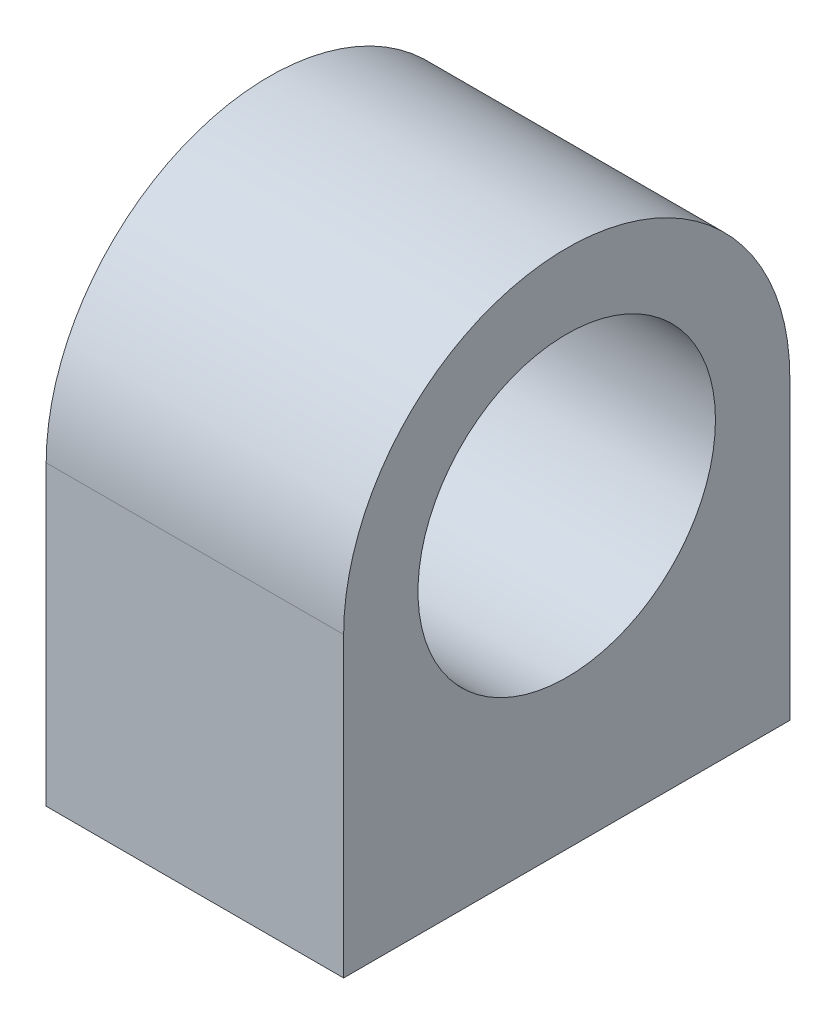
SolidWorks part; units mm, degrees
ref_plane "Front Plane" through (0, 0, 0) normal (0, 0, 1) x (1, 0, 0)
ref_plane "Top Plane" through (0, 0, 0) normal (0, 1, 0) x (1, 0, 0)
ref_plane "Right Plane" through (0, 0, 0) normal (1, 0, 0) x (0, 0, -1)
sketch "Sketch1" plane through (0, 0, 0) normal (1, 0, 0) x (0, 0, -1)
  line L0 (-0.75, 1) -> (-0.75, 0)
  line L1 (-0.75, 0) -> (0.75, 0)
  line L2 (0.75, 0) -> (0.75, 1)
  arc A0 (0.75, 1) -> (-0.75, 1) centre (0, 1) ccw
  circle A1 centre (0, 1) radius 0.5
  dimension "D1" = 1.5
  dimension "D2" = 1
  dimension "D3" = 1
extrude "Boss-Extrude1" add sketch "Sketch1" along normal mid plane 1
hole_wizard "Hole1" positions "Sketch2" profile "Sketch3" legacy
sketch "Sketch2" plane through (0, 0, 0) normal (0, -1, 0) x (-1, 0, 0)
  point P0 (0, -0.5)
  point P2 (0, 0.5)
  point P5 (0, 0)
  dimension "D1" = 1
  dimension "D2" = 0.5
sketch "Sketch3" plane through (0, 0, 0.5) normal (1, 0, 0) x (0, 0, -1)
  line L0 (0, 0) -> (0, 0.5)
  line L1 (0, 0.5) -> (0.125, 0.5)
  line L2 (0.125, 0.5) -> (0.125, 0)
  line L3 (0.125, 0) -> (0, 0)
  line L4 (0, 110) -> (0, -10) construction
  dimension "Diameter" = 0.25
  dimension "Depth" = 0.5
